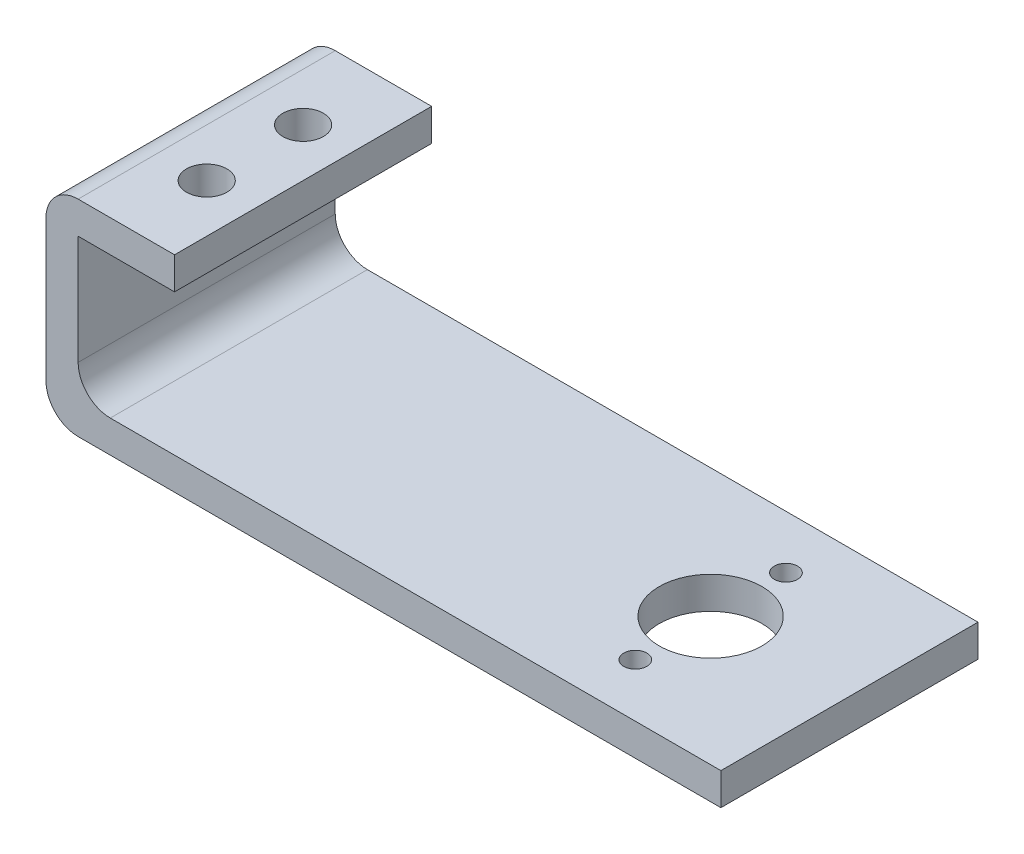
SolidWorks part; units mm, degrees
ref_plane "Front Plane" through (0, 0, 0) normal (0, 0, 1) x (1, 0, 0)
ref_plane "Top Plane" through (0, 0, 0) normal (0, 1, 0) x (1, 0, 0)
ref_plane "Right Plane" through (0, 0, 0) normal (1, 0, 0) x (0, 0, -1)
sketch "Sketch1" plane through (0, 0, 0) normal (0, 0, 1) x (1, 0, 0)
  line L0 (-17.0593, -16.2689) -> (-29.7593, -16.2689)
  line L1 (-29.7593, -16.2689) -> (-29.7593, -36.5889)
  line L2 (-29.7593, -36.5889) -> (36.9157, -36.5889)
  line L3 (-17.0593, -19.4439) -> (-26.5843, -19.4439)
  line L4 (-26.5843, -19.4439) -> (-26.5843, -33.4139)
  line L5 (-26.5843, -33.4139) -> (36.9157, -33.4139)
  line L6 (-17.0593, -16.2689) -> (-17.0593, -19.4439)
  line L7 (36.9157, -36.5889) -> (36.9157, -33.4139)
  line L8 (151.2157, -19.4439) -> (-26.5843, -19.4439) construction
  dimension "D2" = 12.7
  dimension "D3" = 13.97
  dimension "D4" = 63.5
  dimension "D1" = 3.175
extrude "Boss-Extrude1" add sketch "Sketch1" along normal blind 25.4
hole_wizard "Ø4.0mm Dowel Hole1" positions "Sketch6" profile "Sketch5" hole size "Ø4.0" standard "ANSI Metric"
sketch "Sketch6" plane through (0, -16.2689, 0) normal (0, 1, 0) x (1, 0, 0)
  line L1 (-17.0593, -25.4) -> (-17.0593, 0) construction
  line L2 (-17.0593, 0) -> (-29.7593, 0) construction
  point P0 (-21.8218, -7.9375)
  point P2 (-21.8218, -17.4625)
  dimension "D1" = 4.7625
  dimension "D2" = 9.525
  dimension "D3" = 7.9375
sketch "Sketch5" plane through (-21.8218, -16.2689, 7.9375) normal (1, 0, 0) x (0, 0, 1)
  line L0 (0, 0) -> (0, 3.175)
  line L1 (0, 3.175) -> (2, 3.175)
  line L2 (2, 3.175) -> (2, 0)
  line L5 (2, 0) -> (0, 0)
  line L11 (0, -6.35) -> (0, 107.95) construction
  dimension "Thru Hole Dia." = 4
  dimension "Thru Hole Depth" = 3.175
sketch "Sketch7" plane through (0, -36.5889, 0) normal (0, -1, 0) x (1, 0, 0)
  line L0 (-29.7593, 25.4) -> (36.9157, 25.4) construction
  line L2 (-26.5843, 25.4) -> (-26.5843, 0) construction
  circle A0 centre (23.1997, 12.7) radius 5.08
  circle A1 centre (23.1997, 12.7) radius 7.4422 construction
  circle A2 centre (23.1997, 5.2578) radius 1.143
  circle A3 centre (23.1997, 20.1422) radius 1.143
  dimension "D3" = 10.16
  dimension "D4" = 14.8844
  dimension "D5" = 2.286
  dimension "D1" = 12.7
  dimension "D2" = 49.784
extrude "Cut-Extrude1" cut sketch "Sketch7" against normal up to next
fillet "Fillet1" radius 3.175 3 edges at (-29.7593, -16.2689, 12.7) (-26.5843, -33.4139, 12.7) (-29.7593, -36.5889, 12.7)
